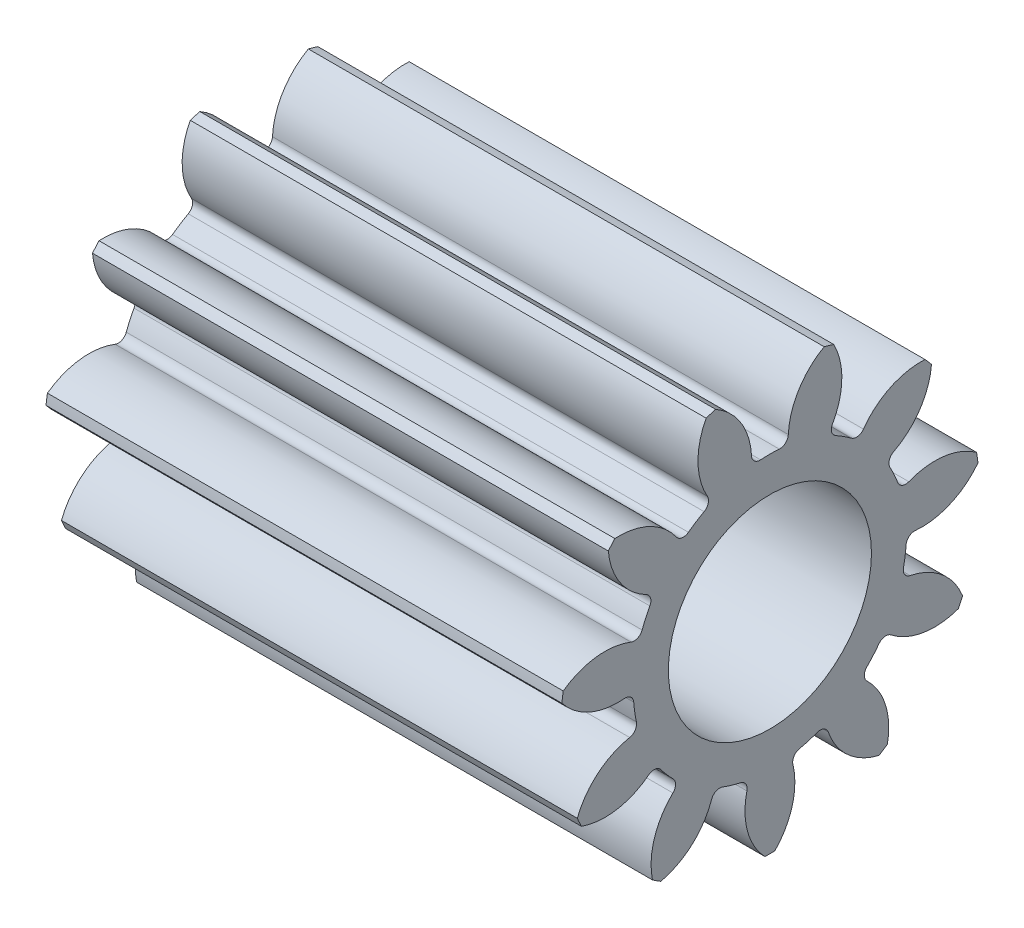
SolidWorks part; units mm, degrees
ref_plane "Plane1" through (0, 0, 0) normal (0, 0, 1) x (1, 0, 0)
ref_plane "Plane2" through (0, 0, 0) normal (0, 1, 0) x (1, 0, 0)
ref_plane "Plane3" through (0, 0, 0) normal (1, 0, 0) x (0, 0, -1)
other "Configuration Table"
sketch "HoldingSke" plane through (0, 0, 0) normal (0, 1, 0) x (1, 0, 0)
  line L0 (0, 0) -> (797.8666, -155.0896)
  line L1 (-15, 0) -> (100, 0) construction
  line L2 (0, 0) -> (-2.1039, 2.3779)
  line L3 (0, 0) -> (-11.863, 4.5341)
  line L4 (0, 0) -> (8.4773, 1.6478)
  line L5 (0, 0) -> (-47.5972, -17.7524)
  line L6 (0, 0) -> (-10.5278, -7.1032)
  line L7 (-2.1039, 2.3779) -> (8.8308, 51.9873)
  line L8 (-76.2, 54.61) -> (-75.184, 54.61)
  line L9 (-71.009, 38.7566) -> (-53.1078, 45.2721)
  line L10 (-76.2, 71.12) -> (104.1128, 71.12)
  line L11 (0, 0) -> (-12.7, 0)
  line L12 (-76.2, 101.6) -> (-76.1716, 101.6)
  line L13 (24.9733, 27.94) -> (52.9518, 28.4284)
  line L14 (24.9733, 27.94) -> (25.0241, 27.9398)
  line L15 (24.9733, 27.94) -> (100.4021, 29.52)
  circle A0 centre (0, 0) radius 0.3969
  circle A1 centre (0, 0) radius 3.3623
  circle A2 centre (0, 0) radius 38.1
  circle A3 centre (0, 0) radius 0.3969
  dimension "MHD" = 6.7246
  dimension "Hub_dia" = 76.2
  dimension "Bore" = 0.7937
  dimension "MBD" = 0.7937
  dimension "Num_teeth" = 11
  dimension "Pitch" = 812.8
  dimension "Overall_len" = 50.8
  dimension "Show_teeth" = 11
  dimension "Thickness" = 12.7
  dimension "OAL" = 50.8003
  dimension "T_dim" = 1.016
  dimension "Ap" = 20
  dimension "H" = 19.05
  dimension "Pitch_radius" = 180.3128
  dimension "Width" = 12.7
  dimension "Backlash" = 0.0284
  dimension "Addendum_fac" = 1
  dimension "Dedendum_fac" = 1.2
  dimension "Clearance_fac" = 0.2
  dimension "Dedendum_add" = 0.0508
sketch "BasProSke" plane through (0, 0, 0) normal (0, 1, 0) x (1, 0, 0)
  line L0 (-10, 0) -> (60, 0) construction
  line L1 (0, 0) -> (0, 5.1594)
  line L2 (0, 0) -> (12.7, 0)
  line L3 (12.7, 0) -> (12.7, 5.1594)
  line L4 (12.7, 5.1594) -> (0, 5.1594)
  dimension "Thickness" = 12.7
  dimension "Diameter" = 10.3187
revolve "Base-Revolve" add sketch "BasProSke" angle 360 about L0
sketch "TooCutSke" plane through (0, 0, 0) normal (1, 0, 0) x (0, 0, -1)
  line L1 (0, 0) -> (0, 107) construction
  line L2 (0, 0) -> (-0.671, 4.3138) construction
  line L3 (0, 0) -> (-2.4387, 8.3055) construction
  line L4 (-0.671, 4.3138) -> (-1.2194, 4.1527) construction
  arc A0 (0.4557, 3.3313) -> (-0.4557, 3.3313) centre (0, 0) ccw
  arc A1 (1.3674, 5.0012) -> (-1.3674, 5.0012) centre (0, 0) ccw
  circle A2 centre (0, 0) radius 4.3656 construction
  circle A3 centre (0, 0) radius 4.1023 construction
  arc A4 (-0.4557, 3.3313) -> (-1.3674, 5.0012) centre (-2.1969, 3.4645) ccw
  arc A5 (1.3674, 5.0012) -> (0.4557, 3.3313) centre (2.1969, 3.4645) ccw
  dimension "Root_dia" = 6.7246
  dimension "Overcut_dia" = 10.3696
  dimension "Pitch_dia" = 8.7312
  dimension "Base_dia" = 8.2047
  dimension "Flank_rad" = 1.7463
  dimension "Half_ang" = 16.364
  dimension "Half_CT" = 0.5715
extrude "ToothCut" cut sketch "TooCutSke" along normal through all
fillet "Breaks" [suppressed] radius 0.0159
fillet "RootFillets" radius 0.2095 2 edges at (6.35, 3.3313, -0.4557) (6.35, 3.3313, 0.4557)
pattern_circular "TeethCuts" count 11 every 32.727 about axis through (-10, 0, 0) along (1, 0, 0) of "ToothCut", "RootFillets", "Breaks"
sketch "HubNeaOneSke" plane through (0, 0, 0) normal (-1, 0, 0) x (0, 0, 1)
  circle A0 centre (0, 0) radius 3.3623
  dimension "Diameter" = 6.7246
extrude "HubNearOne" [suppressed] add sketch "HubNeaOneSke" along normal blind 38.1003
sketch "HubNeaBotSke" plane through (0, 0, 0) normal (-1, 0, 0) x (0, 0, 1)
  circle A0 centre (0, 0) radius 3.3623
  dimension "Diameter" = 6.7246
extrude "HubNearBoth" [suppressed] add sketch "HubNeaBotSke" along normal blind 19.0501
ref_plane "FarPln" through (12.7, 0, 0) normal (1, 0, 0) x (0, 0, -1)
sketch "HubFarSke" plane through (12.7, 0, 0) normal (1, 0, 0) x (0, 0, -1)
  circle A0 centre (0, 0) radius 3.3623
  dimension "Diameter" = 6.7246
extrude "HubFar" [suppressed] add sketch "HubFarSke" along normal blind 19.0501
sketch "BorSke" plane through (0, 0, 0) normal (1, 0, 0) x (0, 0, -1)
  circle A0 centre (0, 0) radius 0.3969
  dimension "Diameter" = 0.7937
extrude "Bore" [suppressed] cut sketch "BorSke" along normal mid plane 101.6005
sketch "KeySke" plane through (0, 0, 0) normal (1, 0, 0) x (0, 0, -1)
  line L0 (-0.127, 0) -> (-0.127, 0.6191)
  line L1 (-0.127, 0.6191) -> (0.127, 0.6191)
  line L2 (0.127, 0.6191) -> (0.127, 0)
  line L3 (0, 0) -> (0, 34) construction
  line L4 (-0.127, 0) -> (0.127, 0)
  dimension "Offset" = 0.6191
  dimension "Width" = 0.254
extrude "Keyway" [suppressed] cut sketch "KeySke" along normal mid plane 101.6005
pattern_circular "Keyway2" [suppressed] count 2 every 90 about axis through (-10, 0, 0) along (1, 0, 0)
sketch "Sketch1" plane through (12.7, 0, 0) normal (1, 0, 0) x (0, 0, -1)
  circle A0 centre (0, 0) radius 2.5
  dimension "D1" = 5
extrude "Cut-Extrude1" cut sketch "Sketch1" against normal up to next
equation "' \"Pitch@HoldingSke\" = 4"
equation "' \"Num_teeth@HoldingSke\" = 12"
equation "' \"Ap@HoldingSke\" =  20"
equation "' \"Ap@HoldingSke\" = 20"
equation "' \"Width@HoldingSke\" = 0.5"
equation "' \"Hub_dia@HoldingSke\"= 1"
equation "' \"Hub_dia@HoldingSke\" = 1"
equation "' \"Overall_len@HoldingSke\" = 1.0"
equation "' \"Bore@HoldingSke\" = 0.75"
equation "' \"T_dim@HoldingSke\" = 0.85"
equation "' \"Width@KeySke\" = 0.25"
equation "' \"Show_teeth@HoldingSke\" = 13"
equation "' \"Backlash@HoldingSke\" = 0.009"
equation "' \"Addendum_fac@HoldingSke\" = 1.0"
equation "' \"Dedendum_fac@HoldingSke\" = 1.25"
equation "' \"Dedendum_add@HoldingSke\" = 0.00005"
equation "' \"Clearance_fac@HoldingSke\" = 0.25"
equation "' \"Pitch@HoldingSke\" = 0.5"
equation "' \"Num_teeth@HoldingSke\" = 23"
equation "' \"Show_teeth@HoldingSke\" = 23"
equation "' \"Backlash@HoldingSke\" = 0.0375"
equation "\"Overcut_dia@TooCutSke\" = (\"Num_teeth@HoldingSke\" + 2 * \"Addendum_fac@HoldingSke\") / \"Pitch@HoldingSke\" + 0.002"
equation "\"Pitch_dia@TooCutSke\" = \"Num_teeth@HoldingSke\" / \"Pitch@HoldingSke\""
equation "\"Base_dia@TooCutSke\" = \"Num_teeth@HoldingSke\" / \"Pitch@HoldingSke\" * cos((\"Ap@HoldingSke\"  * 3.14159265 / 180))"
equation "\"Root_dia@TooCutSke\" = (\"Num_teeth@HoldingSke\" + 2) / \"Pitch@HoldingSke\" - 2 * (\"Addendum_fac@HoldingSke\" + \"Dedendum_fac@HoldingSke\") / \"Pitch@HoldingSke\" - \"Dedendum_add@HoldingSke\" * 2"
equation "\"Half_ang@TooCutSke\" = 180 / \"Num_teeth@HoldingSke\""
equation "\"Half_CT@TooCutSke\" = \"Num_teeth@HoldingSke\" / \"Pitch@HoldingSke\" * sin((3.14159265 / 2 / \"Num_teeth@HoldingSke\")) / 2 - 7 * \"Backlash@HoldingSke\" / 4"
equation "\"Flank_rad@TooCutSke\" = \"Num_teeth@HoldingSke\" / \"Pitch@HoldingSke\" / 5"
equation "\"Radius@RootFillets\" = \"Clearance_fac@HoldingSke\" / \"Pitch@HoldingSke\" + \"Dedendum_add@HoldingSke\""
equation "\"Break_rad@Breaks\" = 0.02 / \"Pitch@HoldingSke\""
equation "\"Thickness@HoldingSke\" = \"Width@HoldingSke\""
equation "\"OAL@HoldingSke\" = \"Thickness@HoldingSke\""
equation "\"MHD@HoldingSke\" = (\"Num_teeth@HoldingSke\" + 2) / \"Pitch@HoldingSke\" - 2 * (\"Addendum_fac@HoldingSke\" + \"Dedendum_fac@HoldingSke\")  / \"Pitch@HoldingSke\" - \"Dedendum_add@HoldingSke\" * 2"
equation "\"MBD@HoldingSke\" = (\"Num_teeth@HoldingSke\" + 2) / \"Pitch@HoldingSke\" - 2 * (\"Addendum_fac@HoldingSke\" + \"Dedendum_fac@HoldingSke\")  / \"Pitch@HoldingSke\" - \"Dedendum_add@HoldingSke\" * 2 - 0.002"
equation "\"MHD@HoldingSke\" = ((sgn( \"MHD@HoldingSke\" - \"Hub_dia@HoldingSke\" )-1)*( \"MHD@HoldingSke\" - \"Hub_dia@HoldingSke\" ))/-2+ \"Hub_dia@HoldingSke\""
equation "\"MBD@HoldingSke\" = ((sgn( \"MBD@HoldingSke\" - \"Bore@HoldingSke\" )-1)*( \"MBD@HoldingSke\" - \"Bore@HoldingSke\" ))/-2+ \"Bore@HoldingSke\""
equation "\"OAL@HoldingSke\" = ((sgn( \"OAL@HoldingSke\" - \"Overall_len@HoldingSke\" )+1)*( \"OAL@HoldingSke\" - \"Overall_len@HoldingSke\" ))/2 + \"Overall_len@HoldingSke\" + 0.000002"
equation "\"Num_teeth@TeethCuts\" = int( \"Show_teeth@HoldingSke\" ) + 1"
equation "\"Num_teeth@TeethCuts\" = ((sgn( \"Num_teeth@TeethCuts\" - \"Num_teeth@HoldingSke\" )-1)*( \"Num_teeth@TeethCuts\" - \"Num_teeth@HoldingSke\" ))/-2+ \"Num_teeth@HoldingSke\""
equation "\"Num_teeth@TeethCuts\" = ((sgn( \"Num_teeth@TeethCuts\" - 2.0)+1)*( \"Num_teeth@TeethCuts\" - 2.0))/2 +2.0"
equation "\"Angle@TeethCuts\" = 360.0 / \"Num_teeth@HoldingSke\""
equation "\"Diameter@BasProSke\" = (\"Num_teeth@HoldingSke\" + 2 * \"Addendum_fac@HoldingSke\") / \"Pitch@HoldingSke\""
equation "\"Thickness@BasProSke\"  = \"Thickness@HoldingSke\""
equation "' \"Fillet_rad@BasProSke\" =  \"Thickness@HoldingSke\" * 0.05"
equation "' \"Fillet_rad@BasProSke\" = \"Thickness@HoldingSke\" * 0.05"
equation "\"MHD@HoldingSke\" = ((sgn( \"MHD@HoldingSke\" - \"Root_dia@TooCutSke\" )-1)*( \"MHD@HoldingSke\" - \"Root_dia@TooCutSke\" ))/-2+ \"Root_dia@TooCutSke\""
equation "\"Diameter@HubNeaOneSke\" = \"MHD@HoldingSke\""
equation "\"Length@HubNearOne\" = \"OAL@HoldingSke\" - \"Thickness@BasProSke\""
equation "\"Diameter@HubNeaBotSke\" = \"MHD@HoldingSke\""
equation "\"Length@HubNearBoth\" = ( \"OAL@HoldingSke\" - \"Thickness@BasProSke\" ) / 2.0"
equation "\"Thickness@FarPln\" = \"Thickness@BasProSke\""
equation "\"Diameter@HubFarSke\" = \"MHD@HoldingSke\""
equation "\"Length@HubFar\" = ( \"OAL@HoldingSke\" - \"Thickness@BasProSke\" ) / 2.0"
equation "\"Diameter@BorSke\" = \"MBD@HoldingSke\""
equation "\"D1@Bore\" = \"OAL@HoldingSke\" * 2.0"
equation "\"D1@Keyway\" = \"OAL@HoldingSke\" * 2.0"
equation "\"Offset@KeySke\" = \"T_dim@HoldingSke\" - \"MBD@HoldingSke\" / 2.0"
equation "\"D1@Sketch1\"=5mm"
